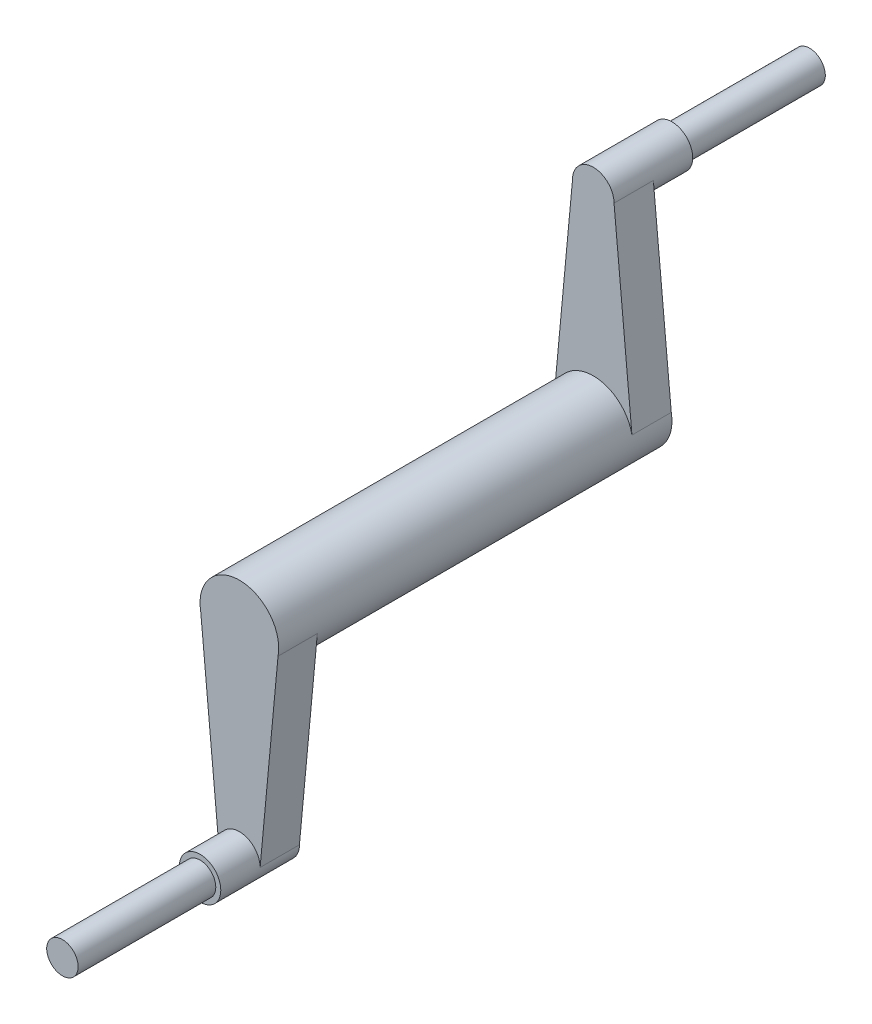
SolidWorks part; units mm, degrees
ref_plane "前视" through (0, 0, 0) normal (0, 0, 1) x (1, 0, 0)
ref_plane "上视" through (0, 0, 0) normal (0, 1, 0) x (1, 0, 0)
ref_plane "右视" through (0, 0, 0) normal (1, 0, 0) x (0, 0, -1)
sketch "草图1" plane through (0, 0, 0) normal (0, 0, 1) x (1, 0, 0)
  circle A0 centre (0, 0) radius 20
extrude "凸台-拉伸2" add sketch "草图1" along normal blind 100 contours A0
sketch "草图2" plane through (0, 0, 100) normal (0, 0, 1) x (1, 0, 0)
  line L0 (-20, 0) -> (-10.5448, -101.3072)
  line L1 (0, 40.8145) -> (0, -76.1698) construction
  line L2 (20, 0) -> (10.5448, -101.3072)
  line L3 (-20, 0) -> (20, 0)
  line L4 (-10.5448, -101.3072) -> (10.5448, -101.3072)
  circle A1 centre (0, 0) radius 20 construction
  dimension "D1" = 5.332
extrude "凸台-拉伸3" add sketch "草图2" against normal blind 20
sketch "草图3" plane through (0, 0, 100) normal (0, 0, 1) x (1, 0, 0)
  line L0 (-10.5448, -101.3072) -> (10.5448, -101.3072) construction
  circle A0 centre (0, -101.3072) radius 10.5448
extrude "凸台-拉伸4" add sketch "草图3" along normal mid plane 40
sketch "草图4" plane through (0, 0, 120) normal (0, 0, 1) x (1, 0, 0)
  circle A0 centre (0, -101.3072) radius 8
extrude "凸台-拉伸5" add sketch "草图4" along normal blind 70
cosmetic thread "装饰螺纹线1" parameters "D1"=10, "D2"=15
sketch "草图5" plane through (0, 0, 0) normal (0, 0, -1) x (-1, 0, 0)
  circle A0 centre (0, 0) radius 20
extrude "凸台-拉伸6" add sketch "草图5" along normal blind 100
sketch "草图6" plane through (0, 0, -100) normal (0, 0, -1) x (-1, 0, 0)
  line L0 (0, 0) -> (0, 93.4628) construction
  line L1 (20, 0) -> (10.5485, 101.3075)
  line L2 (-20, 0) -> (-10.5485, 101.3075)
  line L3 (-10.5485, 101.3075) -> (10.5485, 101.3075)
  line L4 (-20, 0) -> (20, 0)
  circle A0 centre (0, 0) radius 20 construction
  dimension "D1" = 5.33
extrude "凸台-拉伸8" add sketch "草图6" against normal blind 20 contours L1 L3 L2 L4
sketch "草图7" plane through (0, 0, -100) normal (0, 0, -1) x (-1, 0, 0)
  line L0 (-10.5485, 101.3075) -> (10.5485, 101.3075) construction
  circle A0 centre (0, 101.3075) radius 10.5485
extrude "凸台-拉伸9" add sketch "草图7" along normal mid plane 40
sketch "草图8" plane through (0, 0, -120) normal (0, 0, -1) x (-1, 0, 0)
  circle A0 centre (0, 101.3075) radius 8
extrude "凸台-拉伸10" add sketch "草图8" along normal blind 70
cosmetic thread "装饰螺纹线2" parameters "D1"=10, "D2"=15
ref_plane "基准面2" through (0, -16, 0) normal (0, 1, 0) x (1, 0, 0)
sketch "草图9" plane through (0, -16, 0) normal (0, 1, 0) x (1, 0, 0)
  line L0 (0, -33.9278) -> (0, 37.1701) construction
  line L1 (28.4382, 0) -> (-35.3313, 0) construction
  line L2 (6, -8) -> (6, 8)
  line L3 (-6, -8) -> (-6, 8)
  arc A0 (-6, -8) -> (6, -8) centre (0, -8) ccw
  arc A1 (-6, 8) -> (6, 8) centre (0, 8) cw
  point P8 (6, 0)
  dimension "D1" = 12
extrude "切除-拉伸1" cut sketch "草图9" against normal up to next
